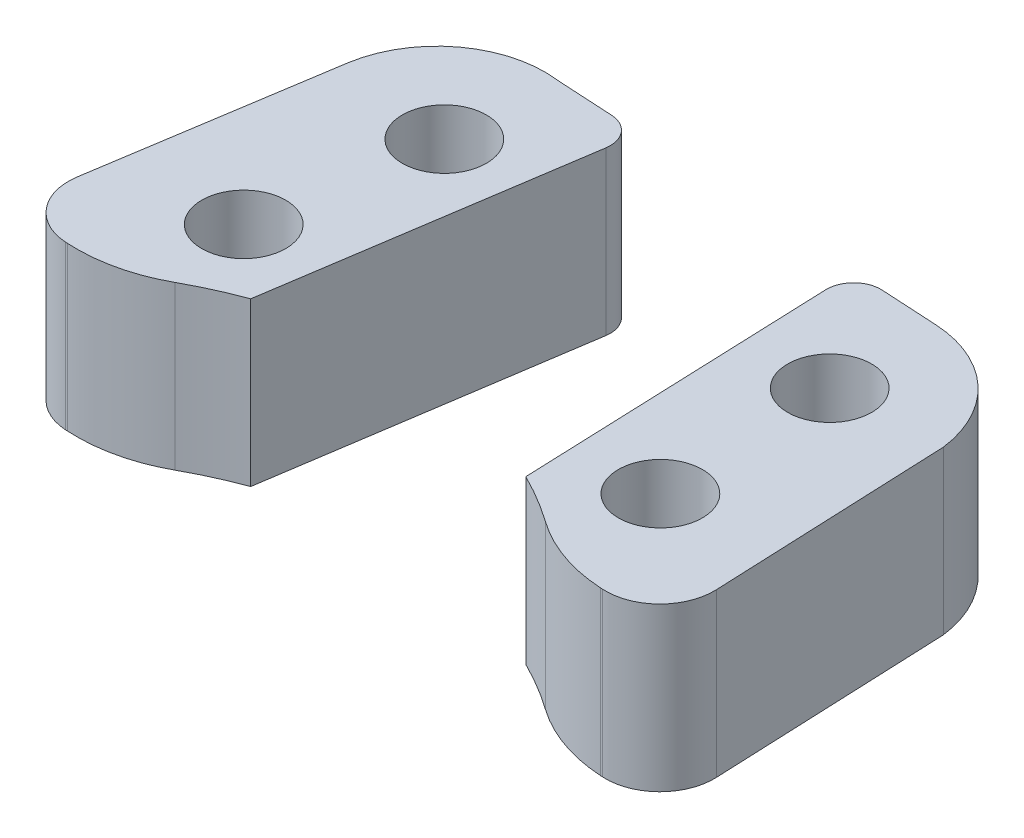
SolidWorks part; units mm, degrees
ref_plane "Płaszczyzna przednia" through (0, 0, 0) normal (0, 0, 1) x (1, 0, 0)
ref_plane "Płaszczyzna górna" through (0, 0, 0) normal (0, 1, 0) x (1, 0, 0)
ref_plane "Płaszczyzna prawa" through (0, 0, 0) normal (1, 0, 0) x (0, 0, -1)
sketch "Szkic1" plane through (0, -18.874, 0) normal (0, -1, 0) x (1, 0, 0)
  line L0 (-376.56, 71.0928) -> (-374.8312, 59.7145)
  line L1 (-366.2405, 60.1988) -> (-365.8012, 71.6995)
  line L2 (-377.4632, 58.4701) -> (-375.7635, 58.5659)
  line L3 (-365.185, 59.1622) -> (-363.4854, 59.2581)
  line L10 (-365.6502, 44.3583) -> (-366.3118, 56.094)
  line L11 (-363.4854, 59.2581) -> (-363.0813, 59.2808)
  line L12 (-359.0404, 63.0505) -> (-358.6721, 71.7981)
  line L13 (-360.7828, 73.8791) -> (-360.8615, 73.8746)
  line L14 (-381.7133, 72.6992) -> (-381.7919, 72.6947)
  line L15 (-383.6554, 70.3897) -> (-382.3062, 61.7389)
  line L16 (-377.8673, 58.4473) -> (-377.4632, 58.4701)
  line L17 (-374.2991, 55.6437) -> (-373.6376, 43.908)
  line L19 (-363.4854, 59.2581) -> (-363.0813, 59.2808)
  line L20 (-359.0404, 63.0505) -> (-358.6721, 71.7981)
  line L21 (-360.7828, 73.8791) -> (-360.8615, 73.8746)
  line L22 (-381.7133, 72.6992) -> (-381.7919, 72.6947)
  line L23 (-383.6554, 70.3897) -> (-382.3062, 61.7389)
  line L24 (-377.8673, 58.4473) -> (-377.4632, 58.4701)
  arc A0 (-374.8312, 59.7145) -> (-375.7635, 58.5659) centre (-375.8198, 59.5643) cw
  arc A1 (-366.2405, 60.1988) -> (-365.185, 59.1622) centre (-365.2413, 60.1607) ccw
  arc A2 (-365.8012, 71.6995) -> (-363.9896, 72.7819) centre (-371.8881, 83.944) ccw
  arc A10 (-363.4854, 59.2581) -> (-366.3118, 56.094) centre (-363.3166, 56.2628) ccw
  arc A11 (-363.0813, 59.2808) -> (-359.0404, 63.0505) centre (-363.3243, 63.592) ccw
  arc A12 (-358.6721, 71.7981) -> (-360.7828, 73.8791) centre (-360.6703, 71.8822) ccw
  arc A13 (-360.8615, 73.8746) -> (-363.9896, 72.7819) centre (-360.5238, 67.8841) ccw
  arc A14 (-378.4822, 71.9649) -> (-363.9896, 72.7819) centre (-371.8881, 83.944) ccw
  arc A15 (-378.4822, 71.9649) -> (-381.7133, 72.6992) centre (-381.3756, 66.7087) ccw
  arc A16 (-381.7919, 72.6947) -> (-383.6554, 70.3897) centre (-381.6793, 70.6979) ccw
  arc A17 (-382.3062, 61.7389) -> (-377.8673, 58.4473) centre (-378.3849, 62.3882) ccw
  arc A18 (-374.2991, 55.6437) -> (-377.4632, 58.4701) centre (-377.2944, 55.4748) ccw
  arc A19 (-373.6376, 43.908) -> (-365.6502, 44.3583) centre (-369.6439, 44.1332) ccw
  arc A21 (-363.0813, 59.2808) -> (-359.0404, 63.0505) centre (-363.3243, 63.592) ccw
  arc A22 (-358.6721, 71.7981) -> (-360.7828, 73.8791) centre (-360.6703, 71.8822) ccw
  arc A23 (-360.8615, 73.8746) -> (-363.9896, 72.7819) centre (-360.5238, 67.8841) ccw
  arc A24 (-378.4822, 71.9649) -> (-376.56, 71.0928) centre (-371.8881, 83.944) ccw
  arc A25 (-378.4822, 71.9649) -> (-381.7133, 72.6992) centre (-381.3756, 66.7087) ccw
  arc A26 (-381.7919, 72.6947) -> (-383.6554, 70.3897) centre (-381.6793, 70.6979) ccw
  arc A27 (-382.3062, 61.7389) -> (-377.8673, 58.4473) centre (-378.3849, 62.3882) ccw
  point P4 (-373.8266, 53.7687)
  point P6 (-366.5706, 54.1777)
  point P12 (-365.4428, 83.6978)
  point P19 (-378.2509, 82.8866)
  point P22 (-366.2825, 59.1004)
  point P29 (-378.3496, 82.8709)
  point P30 (-373.9254, 53.7537)
  point P32 (-366.4707, 54.1738)
  point P33 (-365.3429, 83.694)
  dimension "D2" = 1
  dimension "D1" = 0
extrude "Dodanie-wyciągnięcie1" add sketch "Szkic1" against normal blind 6
sketch "Szkic2" plane through (0, -12.874, 0) normal (0, 1, 0) x (-1, 0, 0)
  circle A0 centre (378.091, 62.4157) radius 1.55 construction
  circle A1 centre (379.0676, 68.8419) radius 1.55 construction
  circle A2 centre (363.0211, 63.2653) radius 1.55 construction
  circle A3 centre (362.773, 69.7605) radius 1.55 construction
  circle A4 centre (378.091, 62.4157) radius 1.55
  circle A5 centre (379.0676, 68.8419) radius 1.55
  circle A6 centre (363.0211, 63.2653) radius 1.55
  circle A7 centre (362.773, 69.7605) radius 1.55
extrude "Wytnij-wyciągnięcie1" cut sketch "Szkic2" against normal blind 6
